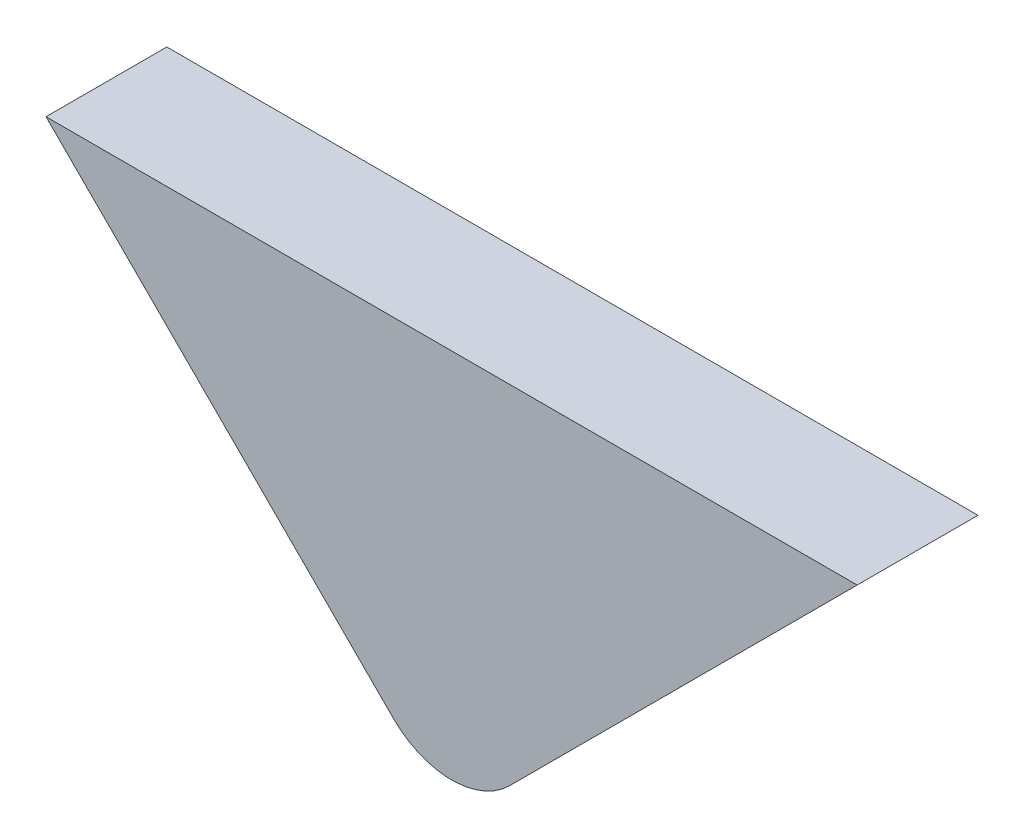
SolidWorks part; units mm, degrees
ref_plane "Front Plane" through (0, 0, 0) normal (0, 0, 1) x (1, 0, 0)
ref_plane "Top Plane" through (0, 0, 0) normal (0, 1, 0) x (1, 0, 0)
ref_plane "Right Plane" through (0, 0, 0) normal (1, 0, 0) x (0, 0, -1)
sketch "Sketch1" plane through (0, 0, 0) normal (0, 0, 1) x (1, 0, 0)
  line L0 (-36.416, 36.416) -> (0, 0) construction
  line L1 (0, 0) -> (36.416, 36.416) construction
  line L2 (0, 0) -> (0, 48.562) construction
  line L3 (4.5657, 9.0912) -> (31.8905, 36.416)
  line L4 (31.8905, 36.416) -> (-31.8905, 36.416)
  line L5 (-31.8905, 36.416) -> (-4.5657, 9.0912)
  arc A0 (-4.5657, 9.0912) -> (4.5657, 9.0912) centre (0, 13.6569) ccw
  dimension "D2" = 7.2
  dimension "D1" = 45
  dimension "D3" = 3.2
  dimension "D4" = 51.5
extrude "Boss-Extrude1" add sketch "Sketch1" along normal blind 9.5
sketch "Sketch5" plane through (2.2627, 2.2627, 0) normal (-0.7071, -0.7071, 0) x (0, 0, 1)
  line L0 (4.75, 48.3) -> (4.75, 9.6569) construction
  line L1 (9.5, 48.3) -> (0, 48.3) construction
  line L2 (9.5, 9.6569) -> (0, 9.6569) construction
  circle A0 centre (4.75, 33.3) radius 1.5
  circle A1 centre (4.75, 18.3) radius 1.5
  dimension "D1" = 3
  dimension "D2" = 15
  dimension "D3" = 15
extrude "Cut-Extrude3" cut sketch "Sketch5" against normal blind 11
mirror "Mirror1" about plane through (0, 0, 0) normal (1, 0, 0) of "Cut-Extrude3"
